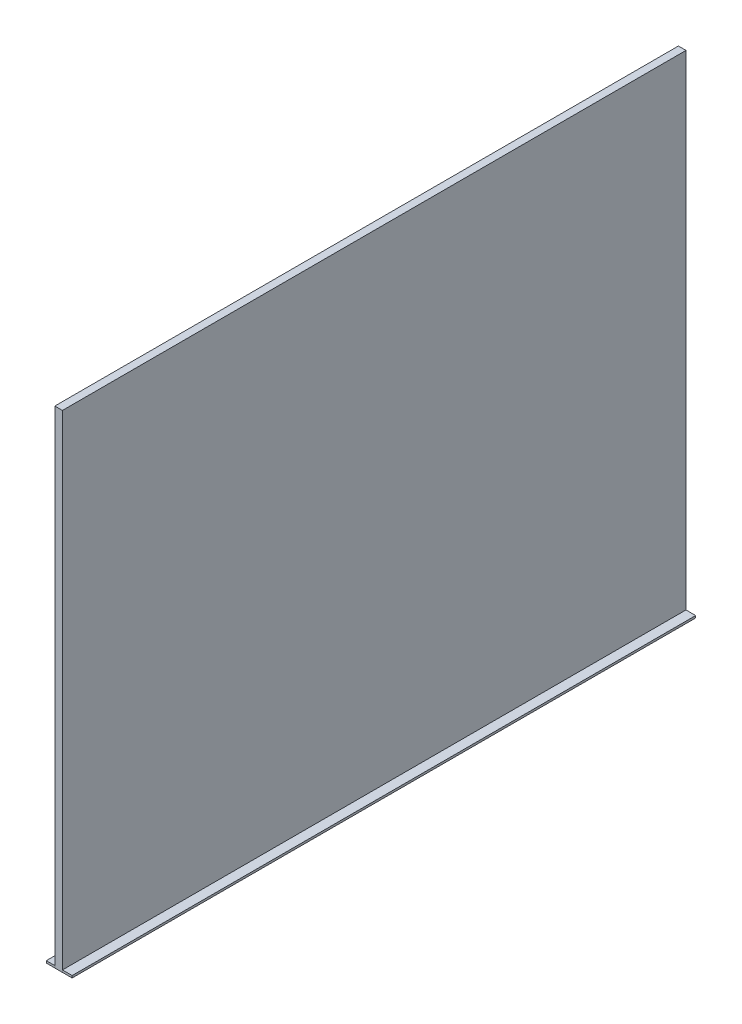
SolidWorks part; units mm, degrees
ref_plane "前视基准面" through (0, 0, 0) normal (0, 0, 1) x (1, 0, 0)
ref_plane "上视基准面" through (0, 0, 0) normal (0, 1, 0) x (1, 0, 0)
ref_plane "右视基准面" through (0, 0, 0) normal (1, 0, 0) x (0, 0, -1)
other "Configuration Table"
sketch "草图1" plane through (0, 0, 0) normal (0, 1, 0) x (1, 0, 0)
  line L1 (0, 0) -> (2.5, 0)
  line L2 (0, 0) -> (0, -205)
  line L3 (0, -205) -> (2.5, -205)
  line L4 (2.5, 0) -> (2.5, -205)
extrude "凸台-拉伸1" add sketch "草图1" along normal blind 160
sketch "草图2" plane through (0, 0, 0) normal (0, 1, 0) x (1, 0, 0)
  line L1 (-2.805, 0) -> (5.6843, 0)
  line L2 (-2.805, 0) -> (-2.805, -204.9844)
  line L3 (-2.805, -204.9844) -> (5.6843, -204.9844)
  line L4 (5.6843, 0) -> (5.6843, -204.9844)
extrude "凸台-拉伸2" add sketch "草图2" along normal blind 0.7
